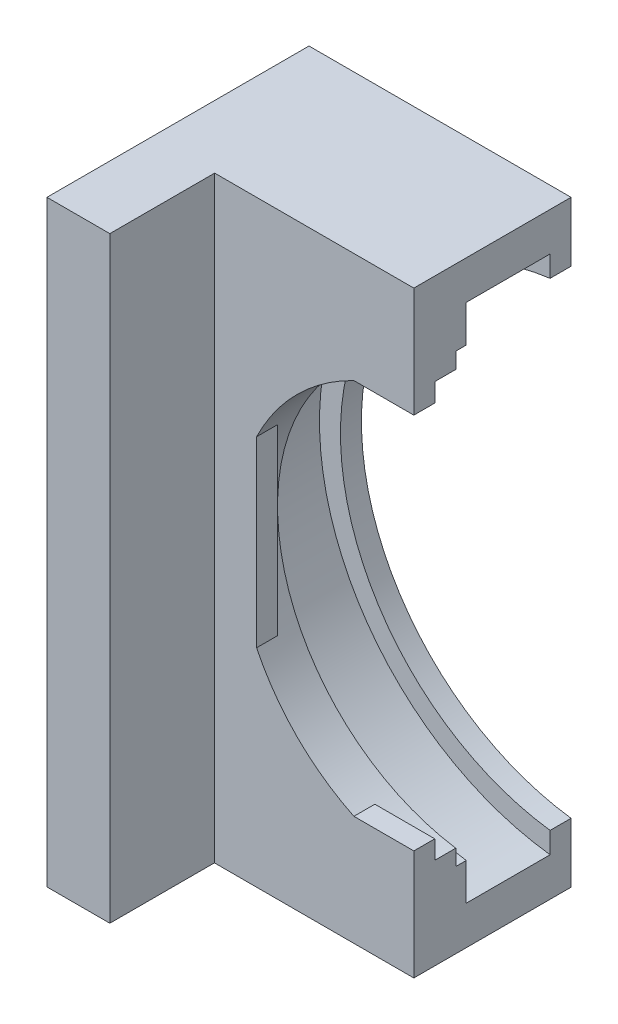
SolidWorks part; units mm, degrees
material "6061 合金"
ref_plane "前视基准面" through (0, 0, 0) normal (0, 0, 1) x (1, 0, 0)
ref_plane "上视基准面" through (0, 0, 0) normal (0, 1, 0) x (1, 0, 0)
ref_plane "右视基准面" through (0, 0, 0) normal (1, 0, 0) x (0, 0, -1)
other "Configuration Table"
sketch "草图1" plane through (0, 0, 0) normal (0, 0, 1) x (1, 0, 0)
  line L1 (-6.25, 14.25) -> (6.25, 14.25)
  line L2 (-6.25, 14.25) -> (-6.25, -14.25)
  line L3 (-6.25, -14.25) -> (6.25, -14.25)
  line L4 (6.25, 14.25) -> (6.25, -14.25)
  line L5 (-6.25, 14.25) -> (6.25, -14.25) construction
  line L6 (-6.25, -14.25) -> (6.25, 14.25) construction
  point P0 (0, 0)
  dimension "D1" = 12.5
  dimension "D2" = 28.5
extrude "凸台-拉伸1" add sketch "草图1" along normal blind 7.5
sketch "草图2" plane through (0, 0, 7.5) normal (0, 0, 1) x (1, 0, 0)
  line L0 (-6.25, 14.25) -> (-3.25, 14.25)
  line L1 (-6.25, 14.25) -> (-6.25, -14.2388)
  line L2 (-3.25, 14.25) -> (-3.25, -14.2388)
  line L3 (-6.25, -14.2388) -> (-3.25, -14.2388)
  line L4 (6.25, 14.25) -> (-6.25, 14.25) construction
  dimension "D1" = 3
extrude "凸台-拉伸2" add sketch "草图2" along normal blind 5
sketch "草图3" plane through (0, 0, 0) normal (0, 0, -1) x (-1, 0, 0)
  line L0 (6.25, 14.25) -> (6.25, -14.25) construction
  circle A0 centre (-7.75, 0) radius 14 construction
  circle A1 centre (-7.75, 0) radius 11.5
  dimension "D1" = 28
  dimension "D2" = 23
extrude "切除-拉伸1" cut sketch "草图3" against normal blind 1
sketch "草图4" plane through (0, 0, 1) normal (0, 0, -1) x (-1, 0, 0)
  circle A0 centre (-7.75, 0) radius 12.5
  dimension "D1" = 25
extrude "切除-拉伸2" cut sketch "草图4" against normal blind 4
sketch "草图5" plane through (0, 0, 5) normal (0, 0, -1) x (-1, 0, 0)
  circle A0 centre (-7.75, 0) radius 10.75
  dimension "D1" = 21.5
extrude "切除-拉伸3" cut sketch "草图5" against normal blind 0.5
sketch "草图6" plane through (0, 0, 5.5) normal (0, 0, -1) x (-1, 0, 0)
  circle A0 centre (-7.75, 0) radius 10
  dimension "D1" = 20
extrude "切除-拉伸4" cut sketch "草图6" against normal blind 1
sketch "草图7" plane through (0, 0, 6.5) normal (0, 0, -1) x (-1, 0, 0)
  line L1 (-16.75, 9) -> (1.25, 9)
  line L2 (-16.75, 9) -> (-16.75, -9)
  line L3 (-16.75, -9) -> (1.25, -9)
  line L4 (1.25, 9) -> (1.25, -9)
  line L5 (-16.75, 9) -> (1.25, -9) construction
  line L6 (-16.75, -9) -> (1.25, 9) construction
  point P0 (-7.75, 0)
  dimension "D1" = 18
  dimension "D2" = 18
extrude "切除-拉伸5" cut sketch "草图7" against normal blind 1
sketch "草图9" plane through (0, 0, 6.5) normal (0, 0, 1) x (1, 0, 0)
  line L2 (3.3911, 9) -> (-1.25, 9)
  line L3 (-1.25, 9) -> (-1.25, 4.3589)
  line L4 (3.3911, 9) -> (-1.25, 9)
  line L5 (-1.25, 9) -> (-1.25, 4.3589)
  line L6 (-1.25, -4.3589) -> (-1.25, -9)
  line L7 (-1.25, -9) -> (3.3911, -9)
  line L8 (-1.25, -4.3589) -> (-1.25, -9)
  line L9 (-1.25, -9) -> (3.3911, -9)
  arc A1 (3.3911, 9) -> (-1.25, 4.3589) centre (7.75, 0) ccw
  arc A2 (3.3911, 9) -> (-1.25, 4.3589) centre (7.75, 0) ccw
  arc A3 (-1.25, -4.3589) -> (3.3911, -9) centre (7.75, 0) ccw
  arc A4 (-1.25, -4.3589) -> (3.3911, -9) centre (7.75, 0) ccw
  dimension "D1" = 0
  dimension "D2" = 0
extrude "凸台-拉伸5" add sketch "草图9" along normal blind 1
